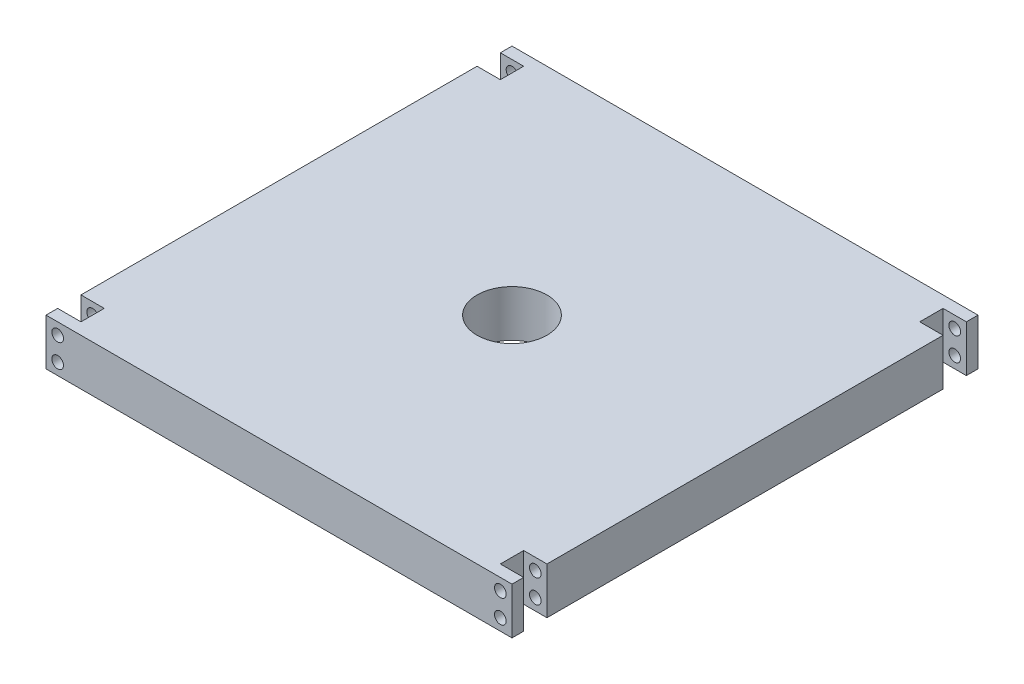
SolidWorks part; units mm, degrees
ref_plane "Plan de face" through (0, 0, 0) normal (0, 0, 1) x (1, 0, 0)
ref_plane "Plan de dessus" through (0, 0, 0) normal (0, 1, 0) x (1, 0, 0)
ref_plane "Plan de droite" through (0, 0, 0) normal (1, 0, 0) x (0, 0, -1)
sketch "Esquisse1" plane through (0, 0, 0) normal (0, 1, 0) x (1, 0, 0)
  line L0 (-100, 95) -> (-90, 95)
  line L1 (100, 100) -> (-100, 100)
  line L2 (100, 100) -> (100, 95)
  line L3 (100, -100) -> (-100, -100)
  line L4 (-100, 100) -> (-100, 95)
  line L5 (100, 100) -> (-100, -100) construction
  line L6 (100, -100) -> (-100, 100) construction
  line L7 (-90, 95) -> (-90, 85)
  line L8 (-90, 85) -> (-100, 85)
  line L9 (-100, 85) -> (-100, -85)
  line L10 (46.6264, 0) -> (-32.5251, 0) construction
  line L11 (-90, -95) -> (-90, -85)
  line L12 (-100, -95) -> (-90, -95)
  line L13 (-90, -85) -> (-100, -85)
  line L14 (0, 41.9741) -> (0, -29.1916) construction
  line L15 (100, -95) -> (90, -95)
  line L16 (90, -95) -> (90, -85)
  line L17 (90, -85) -> (100, -85)
  line L18 (90, 95) -> (90, 85)
  line L19 (100, 95) -> (90, 95)
  line L20 (90, 85) -> (100, 85)
  line L21 (-100, -95) -> (-100, -100)
  line L22 (100, -95) -> (100, -100)
  line L23 (100, 85) -> (100, -85)
  circle A0 centre (0, 0) radius 15
  point P0 (0, 0)
  point P6 (-100, 95)
  dimension "D6" = 30
  dimension "D1" = 200
  dimension "D2" = 200
  dimension "D3" = 5
  dimension "D4" = 10
  dimension "D5" = 10
extrude "BASE" add sketch "Esquisse1" along normal blind 20
sketch "Esquisse2" plane through (0, 0, 100) normal (0, 0, 1) x (1, 0, 0)
  line L0 (0, 30.3759) -> (0, -21.6178) construction
  line L1 (-95, 36.1281) -> (-95, -6.2678) construction
  line L2 (-100, 20) -> (-100, 0) construction
  line L3 (-100, 20) -> (100, 20) construction
  line L4 (-100, 0) -> (100, 0) construction
  circle A0 centre (-95, 15) radius 2.5
  circle A1 centre (-95, 5) radius 2.5
  circle A2 centre (95, 5) radius 2.5
  circle A3 centre (95, 15) radius 2.5
  dimension "D1" = 5
  dimension "D2" = 5
  dimension "D3" = 5
  dimension "D4" = 5
  dimension "D5" = 5
extrude "Enlèv. mat.-Extru.1" cut sketch "Esquisse2" against normal through all
